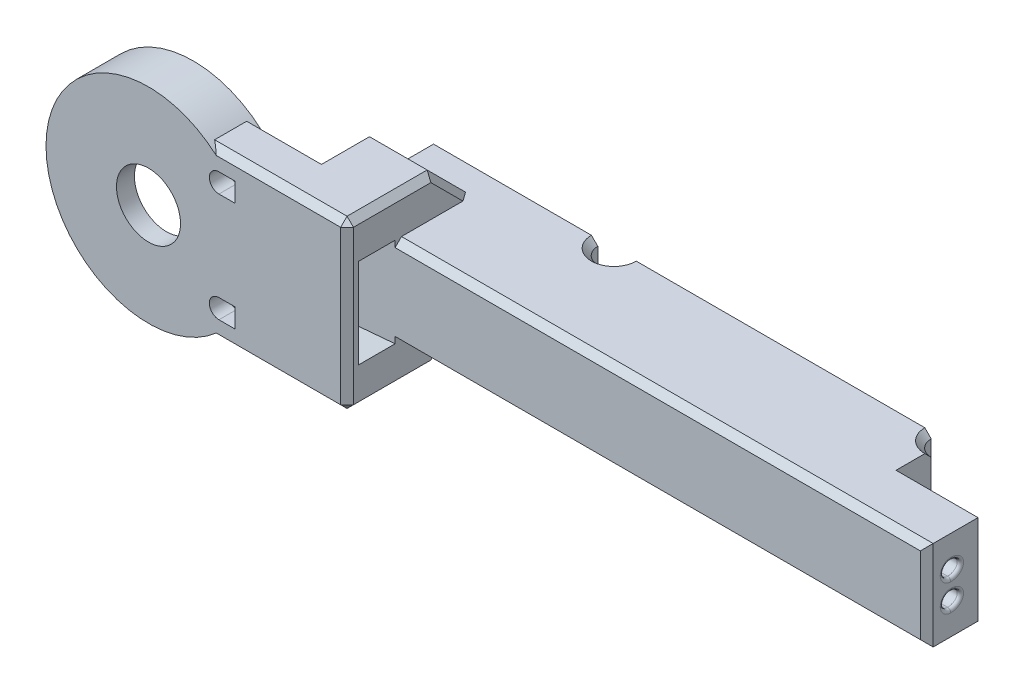
SolidWorks part; units mm, degrees
other "Markup1"
sketch "Sketch31" plane through (-8, 8, 5.05) normal (-0.0551, 0.3318, 0.9417) x (-0.9887, 0.1134, -0.0978)
ref_plane "Front Plane" through (0, 0, 0) normal (0, 0, 1) x (1, 0, 0)
ref_plane "Top Plane" through (0, 0, 0) normal (0, 1, 0) x (1, 0, 0)
ref_plane "Right Plane" through (0, 0, 0) normal (1, 0, 0) x (0, 0, -1)
sketch "Sketch1" plane through (0, 0, 0) normal (0, 0, 1) x (1, 0, 0)
  line L0 (0, 0) -> (15, 0) construction
  line L1 (4.6637, 6.5) -> (15, 6.5)
  line L2 (15, 6.5) -> (15, -6.5)
  line L3 (15, -6.5) -> (4.6637, -6.5)
  line L4 (6.75, 6.5) -> (6.75, -6.5) construction
  line L5 (5.5, 5) -> (6.75, 5)
  line L6 (6.75, 5) -> (6.75, 3.5)
  line L7 (6.75, 3.5) -> (5.5, 3.5)
  line L8 (5.5, -3.5) -> (6.75, -3.5)
  line L9 (6.75, -3.5) -> (6.75, -5)
  line L10 (6.75, -5) -> (5.5, -5)
  circle A0 centre (0, 0) radius 8
  circle A1 centre (0, 0) radius 2.5
  arc A2 (5.5, 5) -> (5.5, 3.5) centre (5.5, 4.25) ccw
  arc A3 (5.5, -3.5) -> (5.5, -5) centre (5.5, -4.25) ccw
  arc A4 (5.5, 3.5) -> (5.5, 5) centre (5.5, 4.25) ccw construction
  arc A5 (5.5, -5) -> (5.5, -3.5) centre (5.5, -4.25) ccw construction
  point P7 (15, 0)
  dimension "D1" = 16
  dimension "D4" = 5
  dimension "D6" = 1.5
  dimension "D7" = 4.25
  dimension "D2" = 15
  dimension "D3" = 13
  dimension "D5" = 6.75
  dimension "D8" = 4.25
  dimension "D9" = 1.25
extrude "Boss-Extrude1" add sketch "Sketch1" along normal blind 3.5 contours A0 L5 L6 L9 L10 L3 L2 L1 | A3 L8 L9 A0 L6 L7 A2 L5 L10 A1
ref_plane "Plane1" through (0, 0, 3.5) normal (0, 0, 1) x (1, 0, 0)
sketch "Sketch39" plane through (0, 0, 0) normal (0, 0, -1) x (-1, 0, 0)
  line L0 (-0.0752, 0) -> (-0.1714, 0) construction
  line L1 (5.75, 0.75) -> (5.75, 2.5)
  line L2 (5.75, 2.5) -> (2.5, 5.75)
  line L3 (2.5, 5.75) -> (-6.75, 5.75)
  line L4 (-6.75, 5.75) -> (-6.75, -5.75)
  line L5 (2.5, -5.75) -> (-6.75, -5.75)
  line L6 (5.75, -2.5) -> (2.5, -5.75)
  line L7 (5.75, 0.75) -> (8.3767, 0.75)
  line L8 (8.3767, 0.75) -> (8.3767, -0.75)
  line L9 (5.75, -0.75) -> (5.75, -2.5)
  line L10 (5.75, -0.75) -> (8.3767, -0.75)
  point P6 (5.75, 0)
  point P15 (-6.75, 0)
  point P19 (8.3767, 0)
  dimension "D1" = 5.75
  dimension "D2" = 5.75
  dimension "D3" = 2.5
  dimension "D4" = 45
  dimension "D5" = 6.75
  dimension "D6" = 0.75
extrude "Cut-Extrude17" cut sketch "Sketch39" against normal blind 2.1
sketch "Sketch38" plane through (15, 0, 0) normal (1, 0, 0) x (0, 0, -1)
  line L0 (-3.5, 6.5) -> (3.25, 6.5)
  line L1 (3.25, 6.5) -> (6.25, 3.5)
  line L2 (6.25, 3.5) -> (8.25, 3.5)
  line L3 (8.25, 3.5) -> (8.25, -3.5)
  line L4 (8.25, -3.5) -> (6.25, -3.5)
  line L5 (6.25, -3.5) -> (3.25, -6.5)
  line L6 (3.25, -6.5) -> (-3.5, -6.5)
  line L7 (0, 6.5) -> (0, -6.5) construction
  line L12 (0, -6.5) -> (0, 6.5)
  line L13 (0, 6.5) -> (-3.5, 6.5)
  line L14 (-3.5, 6.5) -> (-3.5, -6.5)
  line L15 (-3.5, -6.5) -> (0, -6.5)
  line L18 (-3.5, 6.5) -> (-3.5, -6.5)
  point P10 (8.25, 0)
  dimension "D1" = 3.25
  dimension "D2" = 3
  dimension "D3" = 3
  dimension "D4" = 2
  dimension "D5" = 0
extrude "Boss-Extrude11" add sketch "Sketch38" against normal blind 5
sketch "Sketch37" plane through (0, 0, 0) normal (0, 1, 0) x (1, 0, 0)
  line L0 (0, -9.2084) -> (0, 9.2084) construction
  line L3 (-1000, 0) -> (49000, 0) construction
  line L5 (57, 0) -> (57, 50000) construction
  point P4 (0, 0)
  dimension "D1" = 57
ref_plane "Plane2" through (57, 0, 0) normal (1, 0, 0) x (0, 0, -1)
sketch "Sketch6" plane through (15, 0, 0) normal (1, 0, 0) x (0, 0, -1)
  line L1 (3.25, 6.5) -> (-3.5, 6.5)
  line L3 (3.25, -6.5) -> (-3.5, -6.5)
  line L4 (-3.5, 6.5) -> (-3.5, -6.5)
  line L8 (3.25, 6.5) -> (6.25, 3.5)
  line L9 (6.25, 3.5) -> (8.25, 3.5)
  line L10 (0, 8) -> (0, -8) construction
  line L11 (0, 0) -> (8.25, 0) construction
  line L12 (3.25, -6.5) -> (6.25, -3.5)
  line L13 (6.25, -3.5) -> (8.25, -3.5)
  line L14 (8.25, -3.5) -> (8.25, 3.5) construction
  line L15 (3.25, -6.5) -> (6.25, -3.5) construction
  line L16 (8.25, 3.5) -> (6.25, 3.5) construction
  dimension "D1" = 3.25
  dimension "D2" = 3
  dimension "D3" = 3
extrude "Boss-Extrude4" add sketch "Sketch6" along normal up to surface (42 mm away) up to plane "Plane2"
sketch "Sketch7" plane through (0, 0, -8.25) normal (0, 0, -1) x (-1, 0, 0)
  line L1 (-57, -6.5) -> (-48.1, -6.5)
  line L2 (-57, -6.5) -> (-57, 6.5)
  line L3 (-57, 6.5) -> (-48.1, 6.5)
  line L4 (-48.1, -6.5) -> (-48.1, 6.5)
  line L5 (-10, 6.5) -> (-57, 6.5) construction
  dimension "D1" = 8.9
extrude "Cut-Extrude2" cut sketch "Sketch7" against normal blind 4
sketch "Sketch22" plane through (0, 0, 3.5) normal (0, 0, 1) x (1, 0, 0)
  line L1 (15.5, 6.5) -> (57, 6.5)
  line L2 (15.5, 6.5) -> (15.5, -6.5)
  line L3 (15.5, -6.5) -> (57, -6.5)
  line L4 (57, 6.5) -> (57, -6.5)
  line L6 (4.6637, 6.5) -> (57, 6.5) construction
  line L8 (57, -6.5) -> (4.6637, -6.5) construction
  line L9 (10, -3.5) -> (10, 3.5) construction
  dimension "D1" = 5.5
extrude "Cut-Extrude13" cut sketch "Sketch22" against normal blind 3.75 contours L2 L1 L4 L3
sketch "Sketch23" plane through (0, 6.5, 0) normal (0, 1, 0) x (1, 0, 0)
  line L1 (10, 8.25) -> (57, 8.25)
  line L2 (10, 8.25) -> (10, 0.25)
  line L3 (10, 0.25) -> (57, 0.25)
  line L4 (57, 8.25) -> (57, 0.25)
  line L5 (10, 0.25) -> (15.5, 0.25)
  line L6 (10, 0.25) -> (10, 8.25)
  line L7 (10, 8.25) -> (15.5, 8.25)
  line L8 (15.5, 0.25) -> (15.5, 8.25)
  dimension "D2" = 5.5
extrude "Cut-Extrude14" cut sketch "Sketch23" against normal blind 3
mirror "Mirror1" about plane through (0, 0, 0) normal (0, 1, 0) of "Cut-Extrude14"
sketch "Sketch19" plane through (57, 0, 0) normal (1, 0, 0) x (0, 0, -1)
  line L0 (2.125, -3.5) -> (2.125, 3.5) construction
  line L1 (0.25, -3.5) -> (4.25, -3.5) construction
  line L3 (4.25, 3.5) -> (4.25, -3.5) construction
  line L5 (0.25, 3.5) -> (4.25, 3.5) construction
  arc A0 (2.125, -0.475) -> (2.125, -1.625) centre (2.125, -1.05) ccw
  arc A1 (2.125, 1.625) -> (2.125, 0.475) centre (2.125, 1.05) ccw
  arc A2 (2.125, 0.475) -> (2.125, 1.625) centre (2.125, 1.05) ccw construction
  arc A3 (2.125, -1.625) -> (2.125, -0.475) centre (2.125, -1.05) ccw construction
  ellipse E0 centre (2.125, 1.05) end of major axis (2.875, 1.05) minor radius 0.575 (2.125, 0.475) -> (2.125, 1.625) ccw
  ellipse E1 centre (2.125, -1.05) end of major axis (2.875, -1.05) minor radius 0.575 (2.125, -1.625) -> (2.125, -0.475) ccw
  ellipse E2 centre (2.125, 1.05) end of major axis (2.875, 1.05) minor radius 0.575 (2.125, 1.625) -> (2.125, 0.475) ccw construction
  ellipse E3 centre (2.125, -1.05) end of major axis (2.875, -1.05) minor radius 0.575 (2.125, -0.475) -> (2.125, -1.625) ccw construction
  point P11 (2.125, 0)
  dimension "D2" = 1.15
  dimension "D3" = 1.15
  dimension "D1" = 1.05
  dimension "D4" = 2.125
  dimension "D5" = 2.1
  dimension "D6" = 0.75
  dimension "D7" = 0.75
extrude "Cut-Extrude11" cut sketch "Sketch19" against normal through all
sketch "Sketch25" plane through (0, 3.5, 0) normal (0, 1, 0) x (1, 0, 0)
  line L0 (50.6, 7) -> (50.6, 8.25) construction
  line L1 (48.1, 4.25) -> (50.6, 4.25)
  line L2 (48.1, 4.25) -> (48.1, 8.25)
  line L3 (48.1, 8.25) -> (49.35, 8.25)
  line L4 (50.6, 4.25) -> (50.6, 7)
  line L5 (49.35, 8.25) -> (50.6, 8.25) construction
  line L7 (57, 0.25) -> (57, 4.25) construction
  line L8 (10, 8.25) -> (48.1, 8.25) construction
  arc A0 (49.35, 8.25) -> (50.6, 7) centre (50.6, 8.25) ccw
  arc A1 (50.6, 7) -> (49.35, 8.25) centre (50.6, 8.25) ccw construction
  dimension "D1" = 2.5
  dimension "D2" = 6.4
extrude "Boss-Extrude12" add sketch "Sketch25" against normal up to surface (7 mm away) up to face at (32.65, -3.5, -4.75)
sketch "Sketch24" plane through (0, 3.5, 0) normal (0, 1, 0) x (1, 0, 0)
  line L1 (10, 8.25) -> (49.35, 8.25) construction
  line L2 (57, 0.25) -> (57, 4.25) construction
  circle A0 centre (24.575, 8.25) radius 1.25
  dimension "D1" = 2.5
  dimension "D2" = 32.425
extrude "Cut-Extrude15" cut sketch "Sketch24" against normal through all
sketch "Sketch26" plane through (0, -3.5, 0) normal (0, 1, 0) x (1, 0, 0)
  line L0 (35.25, 8.25) -> (35.25, 3.5) construction
  line L2 (57, 0.25) -> (57, 4.25) construction
  line L3 (37.4, 3.5) -> (33.1, 3.5)
  line L4 (37.4, 3.5) -> (37.4, 8.25)
  line L5 (37.4, 8.25) -> (33.1, 8.25)
  line L6 (33.1, 8.25) -> (33.1, 3.5)
  line L8 (25.825, 8.25) -> (49.35, 8.25) construction
  point P9 (35.25, 3.5)
  dimension "D2" = 4.3
  dimension "D3" = 4.75
  dimension "D1" = 21.75
extrude "Cut-Extrude16" cut sketch "Sketch26" along normal blind 1.65
ref_plane "Plane6" through (16.75, 0, 0) normal (1, 0, 0) x (0, 0, -1)
fillet "Fillet8" radius 0.25 8 edges at (10, -1.05, -1.55) (10, 1.05, -1.55) (57, -1.05, -1.55) (57, 1.05, -1.55) (10, -1.05, -2.875) (10, 1.05, -2.875) (57, -1.05, -2.875) (57, 1.05, -2.875)
sketch "Sketch40" plane through (15.5, 0, 0) normal (1, 0, 0) x (0, 0, -1)
  line L0 (-3.5, 6.5) -> (-3.5, -6.5) construction
  line L1 (-2.1, 3.5) -> (0.25, 3.5)
  line L2 (-2.1, 3.5) -> (-2.1, -3.5)
  line L3 (-2.1, -3.5) -> (0.25, -3.5)
  line L4 (0.25, 3.5) -> (0.25, -3.5)
  line L5 (0.25, 3.5) -> (0.25, -3.5) construction
  point P4 (0.25, 0)
  dimension "D1" = 7
  dimension "D2" = 1.4
sketch "Sketch41" plane through (6.75, 0, 0) normal (-1, 0, 0) x (0, 0, 1)
  line L0 (3.5, 4.25) -> (2.1, 4.25) construction
  line L1 (2.1, -4.25) -> (-0.25, -4.25)
  line L2 (2.1, -4.25) -> (2.1, 4.25)
  line L3 (2.1, 4.25) -> (-0.25, 4.25)
  line L4 (-0.25, -4.25) -> (-0.25, 4.25)
  line L6 (2.1, 3.5) -> (2.1, -3.5) construction
  line L7 (3.5, -4.25) -> (2.1, -4.25) construction
  dimension "D1" = 2.35
loft "Cut-Loft1" cut profiles "Sketch41", "Sketch40"
chamfer "Chamfer1" distance 0.5 angle 45 27 edges at (10, 6.5, -1.625) (10, 5, -4.75) (10, 3.5, -7.25) (10, 0, -8.25) (10, -3.5, -7.25) (10, -5, -4.75) (10, -6.5, -1.625) (15.5, -5, -4.75) (15.5, 5, -4.75) (15.5, 6.5, 0.125) (15.5, 0, 3.5) (15.5, -6.5, 0.125) (57, 0, -0.25) (33.1, -3.5, -5.875) (35.25, -3.5, -3.5) (37.4, -3.5, -5.875) (49.7161, -3.5, -7.3661) (49.7161, 3.5, -7.3661) (24.575, 3.5, -7) (24.575, -3.5, -7) (7.3318, -6.5, 0) (7.3318, 6.5, 0) (10.0818, -6.5, 3.5) (10.0818, 6.5, 3.5)
equation "\"d\"= 68mm"
equation "\"D1@Sketch37\"=\"d\"-11"
equation "\"phx\"= \"d\" - 11 - 15.5"
equation "\"middle\"= \"phx\" / 2"
equation "\"D1@Sketch26\"=\"middle\" + 1"
equation "\"D2@Sketch24\"=\"middle\" + \"middle\"/2 + 1.3"
